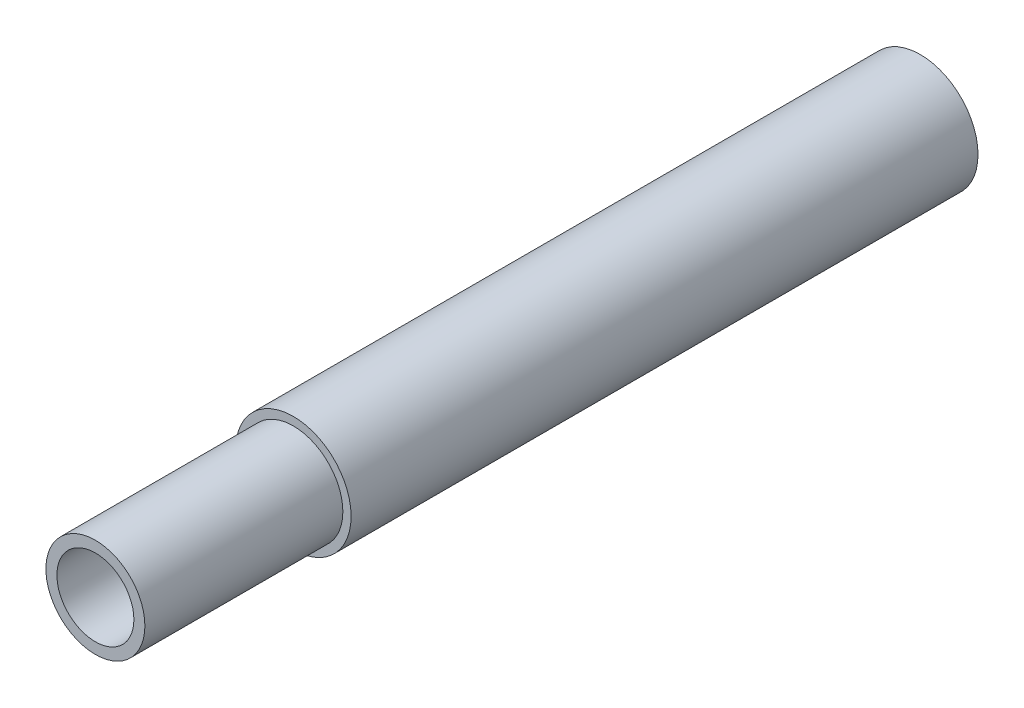
SolidWorks part; units mm, degrees
material "1060 Alloy"
ref_plane "Front Plane" through (0, 0, 0) normal (0, 0, 1) x (1, 0, 0)
ref_plane "Top Plane" through (0, 0, 0) normal (0, 1, 0) x (1, 0, 0)
ref_plane "Right Plane" through (0, 0, 0) normal (1, 0, 0) x (0, 0, -1)
sketch "Sketch2" plane through (0, 0, 0) normal (0, 0, 1) x (1, 0, 0)
  circle A0 centre (0, 0) radius 7
  circle A1 centre (0, 0) radius 10.5
  dimension "D1" = 14
  dimension "D2" = 21
extrude "Boss-Extrude1" add sketch "Sketch2" against normal blind 114
sketch "Sketch4" plane through (0, 0, 0) normal (0, 0, 1) x (1, 0, 0)
  circle A0 centre (0, 0) radius 7
  circle A1 centre (0, 0) radius 9
  dimension "D1" = 14
  dimension "D2" = 18
extrude "Boss-Extrude2" add sketch "Sketch4" along normal blind 36
